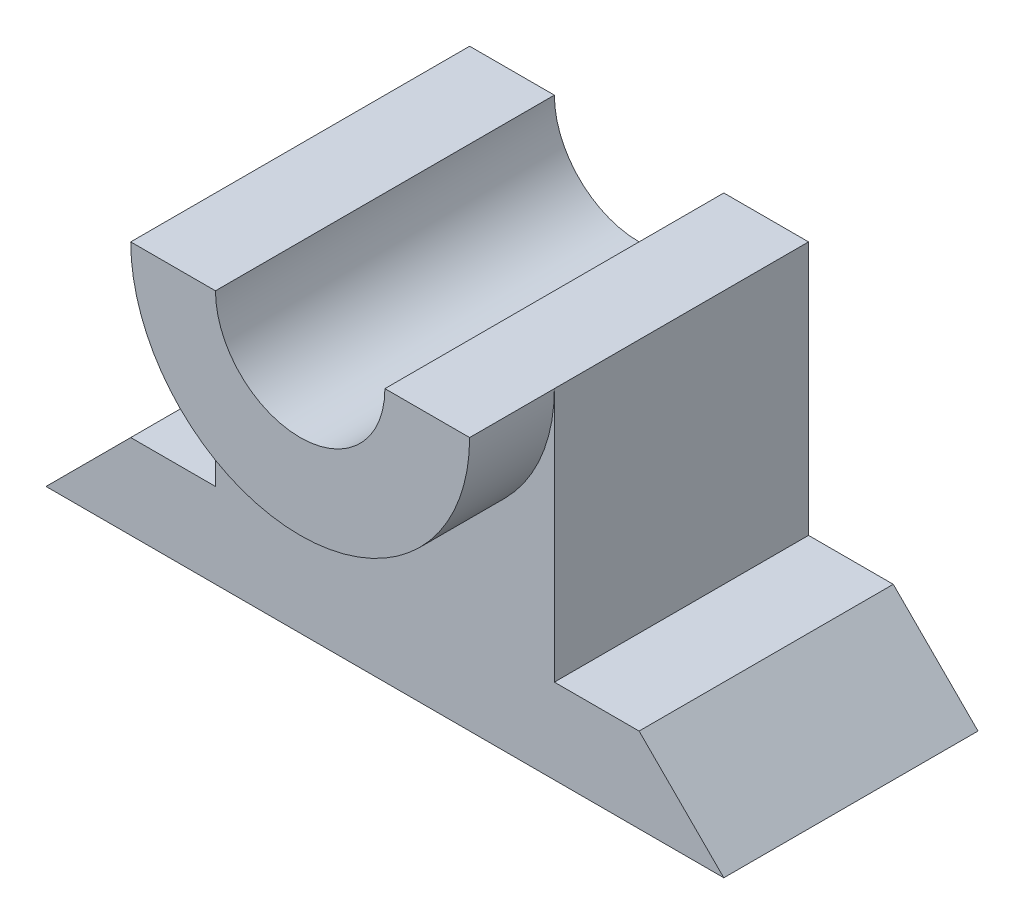
SolidWorks part; units mm, degrees
ref_plane "Front Plane" through (0, 0, 0) normal (0, 0, 1) x (1, 0, 0)
ref_plane "Top Plane" through (0, 0, 0) normal (0, 1, 0) x (1, 0, 0)
ref_plane "Right Plane" through (0, 0, 0) normal (1, 0, 0) x (0, 0, -1)
sketch "Sketch1" plane through (0, 0, 0) normal (0, 0, 1) x (1, 0, 0)
  line L0 (-40, 0) -> (40, 0)
  line L1 (-40, 0) -> (-30, 10)
  line L2 (-30, 10) -> (-20, 10)
  line L3 (-20, 10) -> (-20, 40)
  line L5 (0, 0) -> (0, 54.1693) construction
  line L6 (40, 0) -> (30, 10)
  line L7 (30, 10) -> (20, 10)
  line L8 (20, 10) -> (20, 40)
  line L10 (-20, 40) -> (-10, 40)
  line L11 (20, 40) -> (10, 40)
  arc A2 (-10, 40) -> (10, 40) centre (0, 40) ccw
  point P4 (0, 0)
  dimension "D6" = 10
  dimension "D7" = 10
  dimension "D1" = 80
  dimension "D2" = 10
  dimension "D3" = 10
  dimension "D4" = 45
  dimension "D5" = 40
extrude "Boss-Extrude1" add sketch "Sketch1" against normal blind 30
sketch "Sketch4" plane through (0, 0, 0) normal (0, 0, 1) x (1, 0, 0)
  line L0 (-20, 40) -> (20, 40) construction
  line L1 (-20, 40) -> (-10, 40)
  line L2 (20, 40) -> (10, 40)
  arc A0 (-20, 40) -> (20, 40) centre (0, 40) ccw
  arc A1 (-10, 40) -> (10, 40) centre (0, 40) ccw
extrude "Boss-Extrude2" add sketch "Sketch4" along normal blind 10
